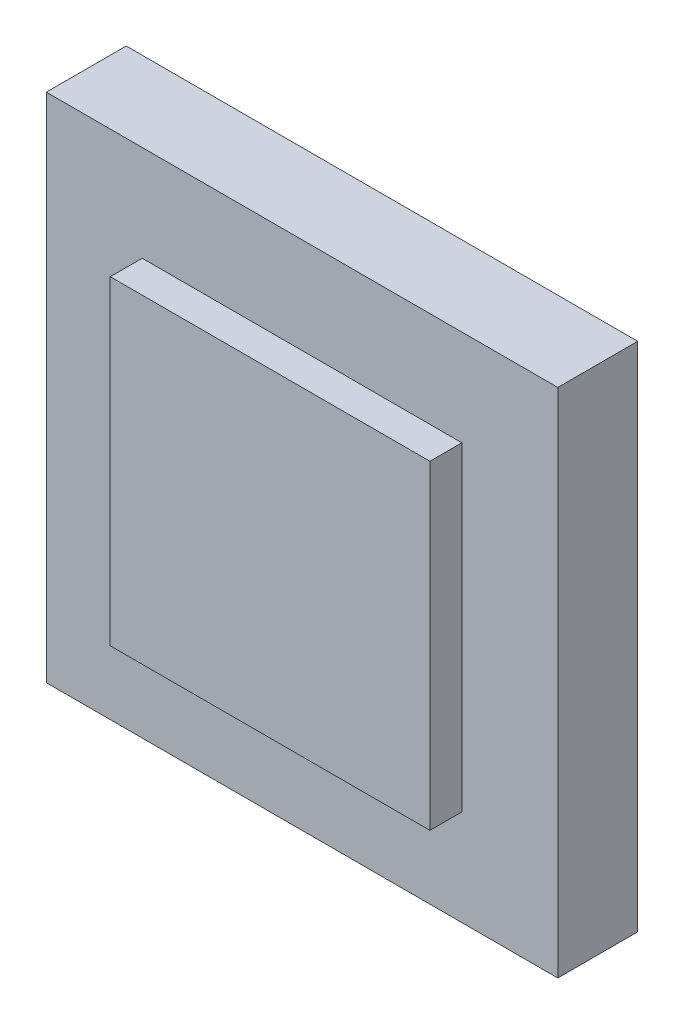
SolidWorks part; units mm, degrees
ref_plane "Front Plane" through (0, 0, 0) normal (0, 0, 1) x (1, 0, 0)
ref_plane "Top Plane" through (0, 0, 0) normal (0, 1, 0) x (1, 0, 0)
ref_plane "Right Plane" through (0, 0, 0) normal (1, 0, 0) x (0, 0, -1)
sketch "Sketch1" plane through (0, 0, 0) normal (0, 0, 1) x (1, 0, 0)
  line L1 (-203.2, -203.2) -> (203.2, -203.2)
  line L2 (-203.2, -203.2) -> (-203.2, 203.2)
  line L3 (-203.2, 203.2) -> (203.2, 203.2)
  line L4 (203.2, -203.2) -> (203.2, 203.2)
  line L5 (-203.2, -203.2) -> (203.2, 203.2) construction
  line L6 (-203.2, 203.2) -> (203.2, -203.2) construction
  point P0 (0, 0)
  dimension "D1" = 406.4
  dimension "D2" = 406.4
extrude "Boss-Extrude1" add sketch "Sketch1" along normal blind 63.5
sketch "Sketch2" plane through (0, 0, 63.5) normal (0, 0, 1) x (1, 0, 0)
  line L1 (-127, -127) -> (127, -127)
  line L2 (-127, -127) -> (-127, 127)
  line L3 (-127, 127) -> (127, 127)
  line L4 (127, -127) -> (127, 127)
  line L5 (-127, -127) -> (127, 127) construction
  line L6 (-127, 127) -> (127, -127) construction
  point P0 (0, 0)
  dimension "D1" = 254
  dimension "D2" = 254
extrude "Boss-Extrude2" add sketch "Sketch2" along normal blind 25.4
